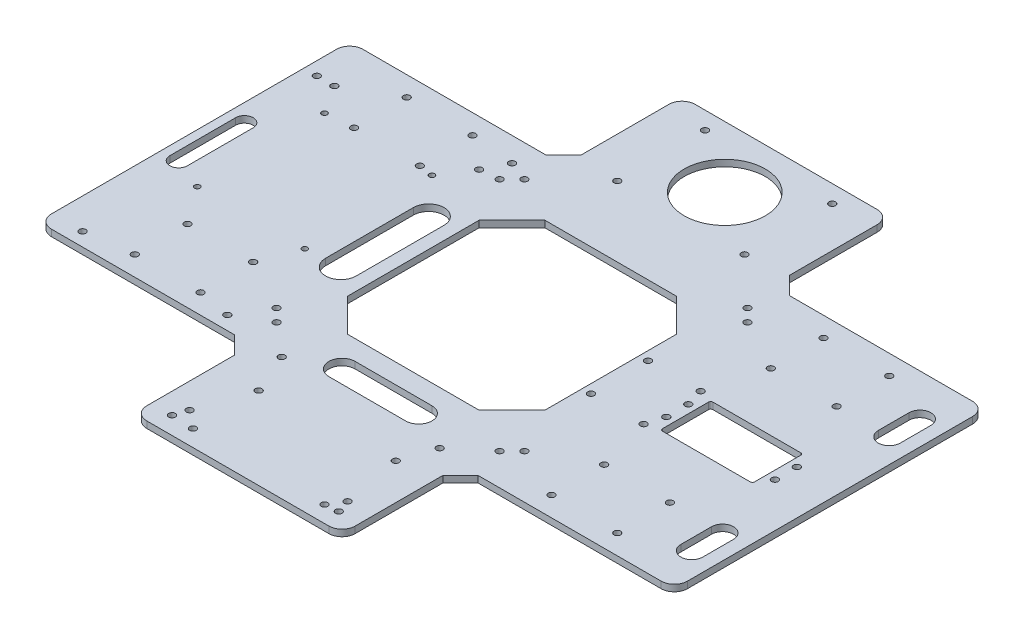
SolidWorks part; units mm, degrees
material "Thornel Mat VMA"
ref_plane "前视基准面" through (0, 0, 0) normal (0, 0, 1) x (1, 0, 0)
ref_plane "上视基准面" through (0, 0, 0) normal (0, 1, 0) x (1, 0, 0)
ref_plane "右视基准面" through (0, 0, 0) normal (1, 0, 0) x (0, 0, -1)
other "Configuration Table"
sketch "草图1" plane through (0, 0, 0) normal (0, 1, 0) x (1, 0, 0)
  line L0 (0, 0) -> (0, 125) construction
  line L1 (-145, -125) -> (145, -125)
  line L2 (-145, -125) -> (-145, 125)
  line L3 (-145, 125) -> (145, 125)
  line L4 (145, -125) -> (145, 125)
  line L5 (-145, -125) -> (145, 125) construction
  line L6 (-145, 125) -> (145, -125) construction
  line L7 (0, 0) -> (145, 0) construction
  line L8 (-47.5, 125) -> (-47.5, 71)
  line L9 (-47.5, 71) -> (-145, 71)
  line L10 (47.5, 71) -> (145, 71)
  line L11 (47.5, 125) -> (47.5, 71)
  line L12 (47.5, -71) -> (145, -71)
  line L13 (47.5, -125) -> (47.5, -71)
  line L14 (-47.5, -71) -> (-145, -71)
  line L15 (-47.5, -125) -> (-47.5, -71)
  point P0 (0, 0)
  dimension "D1" = 290
  dimension "D2" = 250
  dimension "D3" = 142
  dimension "D4" = 95
extrude "凸台-拉伸1" add sketch "草图1" along normal blind 3 contours L15 L1 L13 L12 L4 L10 L11 L3 L8 L9 L2 L14
sketch "草图2" plane through (0, 3, 0) normal (0, 1, 0) x (1, 0, 0)
  line L0 (0, 0) -> (145, 0) construction
  line L1 (145, -71) -> (145, 71) construction
  line L2 (0, 0) -> (0, 125) construction
  line L3 (-47.5, 125) -> (47.5, 125) construction
  line L4 (47.5, 71) -> (145, 71) construction
  circle A0 centre (110, 62) radius 1.5
  circle A1 centre (80, 62) radius 1.5
  circle A2 centre (80, 38) radius 1.5
  circle A3 centre (110, 38) radius 1.5
  circle A4 centre (110, -38) radius 1.5
  circle A5 centre (110, -62) radius 1.5
  circle A6 centre (80, -38) radius 1.5
  circle A7 centre (80, -62) radius 1.5
  circle A8 centre (-80, -62) radius 1.5
  circle A9 centre (-80, -38) radius 1.5
  circle A10 centre (-110, -62) radius 1.5
  circle A11 centre (-110, -38) radius 1.5
  circle A12 centre (-110, 38) radius 1.5
  circle A13 centre (-80, 38) radius 1.5
  circle A14 centre (-80, 62) radius 1.5
  circle A15 centre (-110, 62) radius 1.5
  dimension "D1" = 3
  dimension "D2" = 3
  dimension "D3" = 3
  dimension "D4" = 3
  dimension "D11" = 80
  dimension "D12" = 9
  dimension "D5" = 24
  dimension "D6" = 24
  dimension "D7" = 30
  dimension "D8" = 30
  dimension "D9" = 80
  dimension "D10" = 9
extrude "切除-拉伸1" cut sketch "草图2" against normal blind 3
sketch "草图3" plane through (0, 3, 0) normal (0, 1, 0) x (1, 0, 0)
  line L0 (0, 0) -> (0, 110.5115) construction
  line L1 (0, 0) -> (145, 0) construction
  line L2 (145, -71) -> (145, 71) construction
  line L3 (-86.4083, 97) -> (86.4083, 97) construction
  line L4 (0, 0) -> (0, 108.4938) construction
  line L7 (0, 0) -> (0, -114.288) construction
  circle A5 centre (0, 97) radius 18.5
  circle A33 centre (29, 117) radius 1.5
  circle A34 centre (29, 77) radius 1.5
  circle A35 centre (-29, 77) radius 1.5
  circle A36 centre (-29, 117) radius 1.5
  point P13 (0, 97)
  dimension "D2" = 97
  dimension "D6" = 37
  dimension "D12" = 20
  dimension "D8" = 3
  dimension "D5" = 0
  dimension "D9" = 29
extrude "切除-拉伸2" cut sketch "草图3" against normal blind 10
sketch "草图4" plane through (0, 3, 0) normal (0, 1, 0) x (1, 0, 0)
  line L1 (-45, -45) -> (45, -45)
  line L2 (-45, -45) -> (-45, 45)
  line L3 (-45, 45) -> (45, 45)
  line L4 (45, -45) -> (45, 45)
  line L5 (-45, -45) -> (45, 45) construction
  line L6 (-45, 45) -> (45, -45) construction
  point P0 (0, 0)
  dimension "D1" = 90
  dimension "D2" = 90
extrude "切除-拉伸3" cut sketch "草图4" against normal blind 3
fillet "圆角3" radius 6 8 edges at (-47.5, 1.5, -125) (47.5, 1.5, -125) (145, 1.5, -71) (145, 1.5, 71) (-47.5, 1.5, 125) (47.5, 1.5, 125) (-145, 1.5, 71) (-145, 1.5, -71)
chamfer "倒角1" distance 8 angle 45 4 edges at (47.5, 1.5, 71) (-47.5, 1.5, 71) (47.5, 1.5, -71) (-47.5, 1.5, -71)
sketch "草图7" plane through (0, 3, 0) normal (0, 1, 0) x (1, 0, 0)
  line L0 (0, 0) -> (0, 142.9478) construction
  line L1 (0, 0) -> (-184.5222, 0) construction
  line L2 (-137, -15) -> (-137, 15) construction
  line L5 (-58, -20) -> (-58, 20) construction
  line L6 (-65, -20) -> (-65, 20)
  line L7 (-51, -20) -> (-51, 20)
  line L8 (0, 0) -> (165.4514, 0) construction
  line L14 (-110, 0) -> (-110, 75.2826) construction
  line L15 (134, 38) -> (134, 52) construction
  line L33 (-141, -15) -> (-141, 15)
  line L34 (-133, -15) -> (-133, 15)
  line L35 (63, 0) -> (63, 55.2292) construction
  line L36 (0, -15) -> (172.3256, -15) construction
  line L38 (129, 38) -> (129, 52)
  line L39 (139, 38) -> (139, 52)
  line L40 (134, -38) -> (134, -52) construction
  line L41 (129, -38) -> (129, -52)
  line L42 (139, -38) -> (139, -52)
  arc A2 (-65, -20) -> (-51, -20) centre (-58, -20) ccw
  arc A3 (-51, 20) -> (-65, 20) centre (-58, 20) ccw
  arc A34 (-141, -15) -> (-133, -15) centre (-137, -15) ccw
  arc A35 (-133, 15) -> (-141, 15) centre (-137, 15) ccw
  arc A56 (129, 38) -> (139, 38) centre (134, 38) ccw
  arc A57 (139, 52) -> (129, 52) centre (134, 52) ccw
  arc A58 (129, -38) -> (139, -38) centre (134, -38) cw
  arc A59 (139, -52) -> (129, -52) centre (134, -52) cw
  point P6 (-137, 0)
  point P13 (-58, 0)
  point P21 (134, 45)
  point P37 (134, -45)
  dimension "D2" = 30
  dimension "D5" = 7
  dimension "D8" = 5
  dimension "D10" = 45
  dimension "D9" = 134
  dimension "D3" = 4
  dimension "D23" = 15
  dimension "D1" = 14
  dimension "D4" = 40
  dimension "D6" = 58
  dimension "D7" = 110
  dimension "D20" = 133
  dimension "D24" = 63
extrude "切除-拉伸6" cut sketch "草图7" against normal blind 10
chamfer "倒角2" distance 15 angle 45 4 edges at (45, 1.5, 45) (-45, 1.5, 45) (45, 1.5, -45) (-45, 1.5, -45)
sketch "草图8" plane through (0, 3, 0) normal (0, 1, 0) x (1, 0, 0)
  line L0 (0, 0) -> (0, 168.9929) construction
  line L1 (0, 0) -> (-169.1558, 0) construction
  line L2 (-103, 0) -> (-103, 65.828) construction
  line L3 (-103, -6) -> (-155.6162, -6) construction
  line L4 (0, 0) -> (-184.1789, 0) construction
  line L5 (0, 0) -> (0, 73.477) construction
  line L6 (-55.5, 71) -> (-139, 71) construction
  circle A15 centre (-139, 50) radius 1.5
  circle A16 centre (-131, 50) radius 1.5
  dimension "D2" = 8
  dimension "D4" = 103
  dimension "D5" = 6
  dimension "D6" = 0
  dimension "D7" = 3
  dimension "D8" = 3
  dimension "D11" = 28
  dimension "D12" = 36
  dimension "D10" = 21
extrude "切除-拉伸7" cut sketch "草图8" against normal blind 10
sketch "草图9" plane through (0, 3, 0) normal (0, 1, 0) x (1, 0, 0)
  line L0 (0, 0) -> (0, 165.3902) construction
  line L1 (0, 0) -> (179.4814, 0) construction
  line L2 (50.8431, 56.5) -> (56.5, 50.8431) construction
  line L3 (-62.5, -62.5) -> (62.5, -62.5) construction
  line L4 (-62.5, -62.5) -> (-62.5, 62.5) construction
  line L5 (-62.5, 62.5) -> (62.5, 62.5) construction
  line L6 (62.5, -62.5) -> (62.5, 62.5) construction
  line L7 (-62.5, -62.5) -> (62.5, 62.5) construction
  line L8 (-62.5, 62.5) -> (62.5, -62.5) construction
  line L18 (-50.3018, -50.3018) -> (40.4104, 40.4104) construction
  line L23 (-50.8431, -50.8431) -> (45.8431, 45.8431) construction
  line L24 (-48.3431, 48.3431) -> (48.3431, -48.3431) construction
  line L29 (-52.5221, -52.5221) -> (52.5221, 52.5221) construction
  line L30 (-52.5221, 52.5221) -> (52.5221, -52.5221) construction
  circle A0 centre (50.8431, 56.5) radius 1.5
  circle A1 centre (56.5, 50.8431) radius 1.5
  circle A2 centre (56.5, -50.8431) radius 1.5
  circle A3 centre (50.8431, -56.5) radius 1.5
  circle A4 centre (-50.8431, -56.5) radius 1.5
  circle A5 centre (-56.5, -50.8431) radius 1.5
  circle A6 centre (-56.5, 50.8431) radius 1.5
  circle A7 centre (-50.8431, 56.5) radius 1.5
  circle A8 centre (-38, -117) radius 1.5
  circle A9 centre (38, -117) radius 1.5
  dimension "D3" = 3
  dimension "D4" = 3
  dimension "D6" = 8
  dimension "D9" = 3
  dimension "D11" = 117
  dimension "D1" = 125
  dimension "D2" = 125
  dimension "D5" = 45
  dimension "D7" = 6
  dimension "D8" = 6
  dimension "D10" = 38
extrude "切除-拉伸8" cut sketch "草图9" against normal blind 10
sketch "草图10" plane through (0, 3, 0) normal (0, 1, 0) x (1, 0, 0)
  line L0 (0, 0) -> (173.0266, 0) construction
  line L1 (0, 0) -> (0, 114.2255) construction
sketch "草图11" plane through (0, 3, 0) normal (0, 1, 0) x (1, 0, 0)
  line L0 (0, 0) -> (183.5565, 0) construction
  line L1 (0, 0) -> (0, -155.5612) construction
sketch "草图12" plane through (0, 3, 0) normal (0, 1, 0) x (1, 0, 0)
  line L0 (-17.5, -60) -> (17.5, -60) construction
  line L1 (0, 0) -> (0, -155.5612) construction
  line L2 (-17.5, -54) -> (17.5, -54)
  line L3 (-17.5, -66) -> (17.5, -66)
  line L4 (0, 0) -> (173.0266, 0) construction
  arc A0 (-17.5, -54) -> (-17.5, -66) centre (-17.5, -60) ccw
  arc A1 (17.5, -66) -> (17.5, -54) centre (17.5, -60) ccw
  point P4 (0, -60)
  dimension "D2" = 6
  dimension "D1" = 35
  dimension "D3" = 60
extrude "切除-拉伸9" cut sketch "草图12" against normal blind 10
sketch "草图14" plane through (0, 3, 0) normal (0, 1, 0) x (1, 0, 0)
  line L0 (0, 0) -> (0, -145.4864) construction
  line L1 (0, 0) -> (173.1076, 0) construction
  line L2 (0, -90) -> (89.1596, -90) construction
  circle A0 centre (36, -69) radius 1.5
  circle A1 centre (36, -111) radius 1.5
  circle A2 centre (-36, -111) radius 1.5
  circle A3 centre (-36, -69) radius 1.5
  dimension "D1" = 3
  dimension "D2" = 42
  dimension "D3" = 72
  dimension "D4" = 90
extrude "切除-拉伸10" cut sketch "草图14" against normal blind 10
sketch "草图15" plane through (0, 3, 0) normal (0, 1, 0) x (1, 0, 0)
  line L0 (0, 0) -> (175.5609, 0) construction
  line L1 (0, 0) -> (0, 158.0719) construction
  line L2 (100.11, 0) -> (100.11, 39.6302) construction
  line L3 (79.11, -11.5) -> (121.11, -11.5)
  line L4 (79.11, -11.5) -> (79.11, 11.5)
  line L5 (79.11, 11.5) -> (121.11, 11.5)
  line L6 (121.11, -11.5) -> (121.11, 11.5)
  line L7 (79.11, -11.5) -> (121.11, 11.5) construction
  line L8 (79.11, 11.5) -> (121.11, -11.5) construction
  line L9 (110, 0) -> (110, 79.3701) construction
  circle A0 centre (75.36, 5) radius 1.5
  circle A2 centre (75.36, -5) radius 1.5
  circle A4 centre (124.86, -5) radius 1.5
  circle A5 centre (124.86, 5) radius 1.5
  point P3 (100.11, 0)
  dimension "D3" = 10
  dimension "D4" = 3
  dimension "D5" = 49.5
  dimension "D1" = 42
  dimension "D2" = 23
  dimension "D6" = 9.89
  dimension "D7" = 110
extrude "切除-拉伸11" cut sketch "草图15" against normal blind 10
fillet "圆角4" radius 1 4 edges at (79.11, 1.5, 11.5) (121.11, 1.5, 11.5) (121.11, 1.5, -11.5) (79.11, 1.5, -11.5)
sketch "草图16" plane through (0, 3, 0) normal (0, 1, 0) x (1, 0, 0)
  line L0 (0, 8) -> (-202.0071, 8) construction
  line L1 (0, 8) -> (0, 203.0309) construction
  line L2 (-98, -6.3134) -> (-98, 94.9217) construction
  line L4 (0, 0) -> (0, 8) construction
  line L5 (0, 0) -> (-183.682, 0) construction
  circle A0 centre (-73.5, 37) radius 1.25
  circle A1 centre (-122.5, 37) radius 1.25
  circle A2 centre (-73.5, -21) radius 1.25
  circle A3 centre (-122.5, -21) radius 1.25
  dimension "D1" = 58
  dimension "D2" = 49
  dimension "D3" = 2.5
  dimension "D4" = 98
  dimension "D5" = 8
extrude "切除-拉伸12" cut sketch "草图16" against normal blind 10
sketch "草图19" plane through (0, 3, 0) normal (0, 1, 0) x (1, 0, 0)
  line L0 (0, 0) -> (-178.7427, 0) construction
  line L1 (0, 0) -> (0, 171.7177) construction
  line L2 (-98, -10.9053) -> (-98, 46.7773) construction
  line L3 (-98, -7.4) -> (-15.7423, -7.4) construction
  circle A0 centre (-65, 50) radius 1.5
  circle A1 centre (-131, 50) radius 1.5
  circle A2 centre (-65, -64.8) radius 1.5
  circle A3 centre (-131, -64.8) radius 1.5
  dimension "D1" = 3
  dimension "D2" = 114.8
  dimension "D3" = 66
  dimension "D4" = 98
  dimension "D5" = 7.4
extrude "切除-拉伸13" cut sketch "草图19" against normal blind 10
sketch "草图20" plane through (0, 3, 0) normal (0, 1, 0) x (1, 0, 0)
  line L0 (0, 0) -> (0, 140.7476) construction
  line L1 (0, 0) -> (-188.6657, 0) construction
  circle A0 centre (-60, 60) radius 1.5
  dimension "D1" = 3
  dimension "D2" = 60
  dimension "D3" = 60
extrude "切除-拉伸14" cut sketch "草图20" against normal blind 10
sketch "草图21" plane through (0, 3, 0) normal (0, 1, 0) x (1, 0, 0)
  line L0 (-3, 0) -> (207.5032, 0) construction
  line L1 (-3, 0) -> (-3, -169.1707) construction
  line L2 (0, 0) -> (0, -166.304) construction
  line L3 (-48, -121.5) -> (42, -121.5) construction
  line L4 (-48, -121.5) -> (-48, -66.5) construction
  line L5 (-48, -66.5) -> (42, -66.5) construction
  line L6 (42, -121.5) -> (42, -66.5) construction
  line L7 (-48, -121.5) -> (42, -66.5) construction
  line L8 (-48, -66.5) -> (42, -121.5) construction
  line L9 (0, 0) -> (-28, 0) construction
  circle A0 centre (31, -84) radius 1.5
  circle A1 centre (32, -117.5) radius 1.5
  circle A2 centre (-28, -87.5) radius 1.5
  circle A3 centre (-28, -117.5) radius 1.5
  point P3 (-3, -94)
  dimension "D3" = 3
  dimension "D4" = 3
  dimension "D5" = 3
  dimension "D6" = 3
  dimension "D8" = 17.5
  dimension "D10" = 51
  dimension "D11" = 10
  dimension "D12" = 21
  dimension "D13" = 70
  dimension "D14" = 51
  dimension "D15" = 70
  dimension "D1" = 90
  dimension "D2" = 55
  dimension "D7" = 94
  dimension "D9" = 11
  dimension "D16" = 3
extrude "切除-拉伸15" cut sketch "草图21" against normal blind 10
sketch "草图22" plane through (0, 3, 0) normal (0, 1, 0) x (1, 0, 0)
  line L0 (0, 0) -> (154.1719, 0) construction
  line L1 (61, 0) -> (61, 40.4074) construction
  circle A0 centre (73, 13) radius 1.5
  circle A1 centre (49, 13) radius 1.5
  circle A2 centre (73, -13) radius 1.5
  circle A3 centre (49, -13) radius 1.5
  dimension "D1" = 24
  dimension "D2" = 26
  dimension "D3" = 3
  dimension "D4" = 61
extrude "切除-拉伸16" cut sketch "草图22" against normal blind 10
